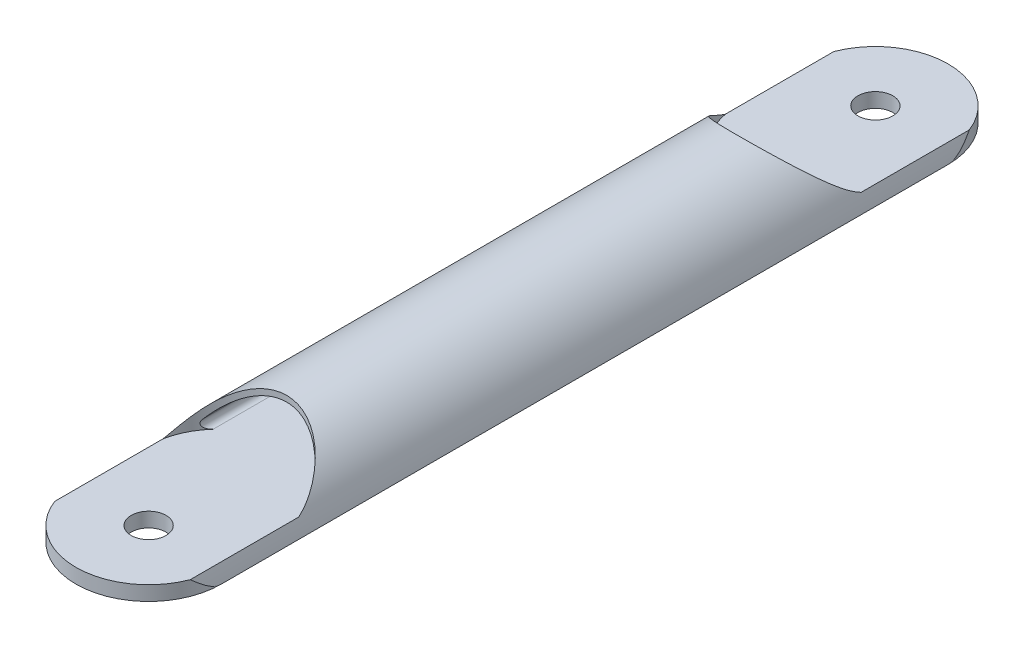
SolidWorks part; units mm, degrees
material "pla filament"
ref_plane "Ön Düzlem" through (0, 0, 0) normal (0, 0, 1) x (1, 0, 0)
ref_plane "Üst Düzlem" through (0, 0, 0) normal (0, 1, 0) x (1, 0, 0)
ref_plane "Sağ Düzlem" through (0, 0, 0) normal (1, 0, 0) x (0, 0, -1)
sketch "Sketch2" plane through (0, 0, 0) normal (0, 0, 1) x (1, 0, 0)
  line L0 (2.6393, 2) -> (47.3607, 2)
  line L1 (0, 0) -> (50, 0)
  arc A0 (0, 0) -> (50, 0) centre (25, -5.625) cw
  arc A1 (2.6393, 2) -> (47.3607, 2) centre (25, -5.625) cw
  dimension "D1" = 25.625
  dimension "D2" = 2
extrude "Boss-Extrude1" add sketch "Sketch2" along normal blind 300
sketch "Sketch3" plane through (0, 0, 300) normal (0, 0, 1) x (1, 0, 0)
  line L0 (0, 0) -> (50, 0) construction
  line L1 (2.2033, 0) -> (47.9135, 0)
  line L2 (2.2033, 0) -> (2.2033, 5)
  line L3 (7.443, 5) -> (42.557, 5)
  line L4 (47.9135, 0) -> (47.9135, 5)
  line L5 (2.6393, 2) -> (47.3607, 2) construction
  line L6 (2.6393, 2) -> (47.3607, 2)
  arc A0 (47.3607, 2) -> (2.6393, 2) centre (25, -5.625) ccw construction
  arc A2 (44.1808, 8.1676) -> (42.557, 5) centre (42.557, 7) cw
  arc A3 (7.443, 5) -> (5.8192, 8.1676) centre (7.443, 7) cw
  arc A4 (47.3607, 2) -> (44.1808, 8.1676) centre (25, -5.625) ccw
  arc A5 (5.8192, 8.1676) -> (2.6393, 2) centre (25, -5.625) ccw
  dimension "D2" = 2
  dimension "D1" = 5
extrude "Boss-Extrude2" add sketch "Sketch3" against normal blind 300 contours L3 A2 A4 L6 A5 A3
sketch "Sketch4" plane through (0, 0, 0) normal (0, -1, 0) x (1, 0, 0)
  line L1 (0, 275) -> (50, 275)
  line L3 (0, 275) -> (50, 275)
  line L4 (0, 275) -> (0, 300)
  line L5 (0, 300) -> (50, 300)
  line L6 (50, 275) -> (50, 300)
  line L7 (50, 300) -> (50, 0) construction
  line L8 (0, 0) -> (50, 0)
  line L9 (0, 0) -> (0, 25)
  line L10 (0, 25) -> (50, 25)
  line L11 (50, 0) -> (50, 25)
  arc A1 (50, 275) -> (0, 275) centre (25, 275) ccw
  arc A3 (0, 25) -> (50, 25) centre (25, 25) ccw
  line M10 (0, 0) -> (50, 0)
  line M11 (50, 0) -> (50, 300)
  line M12 (50, 300) -> (0, 300)
  line M13 (0, 300) -> (0, 0)
  dimension "D1" = 25
extrude "Cut-Extrude2" cut sketch "Sketch4" against normal blind 200 contours A1 M11 M12 | A1 L5 M13 | A3 M13 M10 | A3 L8 M11
sketch "Sketch5" plane through (0, 5, 0) normal (0, 1, 0) x (1, 0, 0)
  line L0 (1.25, -25) -> (1.25, -13.5745)
  line L1 (1.25, -13.5745) -> (14.1618, 8.5504)
  line L2 (14.1618, 8.5504) -> (43.6578, 1.4949)
  line L3 (43.6578, 1.4949) -> (48.75, -2.3752)
  line L4 (48.75, -25) -> (48.75, -2.3752)
  line L5 (0, -150) -> (126.4795, -150) construction
  line L6 (0, -275) -> (0, -25) construction
  line L7 (48.75, -275) -> (48.75, -251.25)
  line L8 (1.25, -275) -> (1.25, -251.25)
  line L9 (48.75, -275) -> (48.75, -297.6248)
  line L10 (43.6578, -301.4949) -> (48.75, -297.6248)
  line L11 (14.1618, -308.5504) -> (43.6578, -301.4949)
  line L12 (1.25, -286.4255) -> (14.1618, -308.5504)
  line L14 (1.25, -25) -> (1.25, -48.75)
  line L16 (48.75, -25) -> (48.75, -48.75)
  line L17 (1.25, -275) -> (1.25, -286.4255)
  arc A3 (48.75, -48.75) -> (1.25, -48.75) centre (25, -48.75) cw
  arc A4 (48.75, -251.25) -> (1.25, -251.25) centre (25, -251.25) ccw
extrude "Cut-Extrude9" cut sketch "Sketch5" along normal blind 200
sketch "Sketch6" plane through (0, 5, 0) normal (0, 1, 0) x (1, 0, 0)
  circle A0 centre (25, -25) radius 6
  circle A1 centre (25, -275) radius 6
  arc A2 (48.3184, -15.9861) -> (1.6816, -15.9861) centre (25, -25) ccw construction
  arc A3 (1.6816, -284.0139) -> (48.3184, -284.0139) centre (25, -275) ccw construction
  point P6 (25, 0)
  point P7 (25, -25)
  point P14 (25, -300)
  dimension "D1" = 12
  dimension "D2" = 25
  dimension "D3" = 12
extrude "Cut-Extrude10" cut sketch "Sketch6" against normal blind 200
